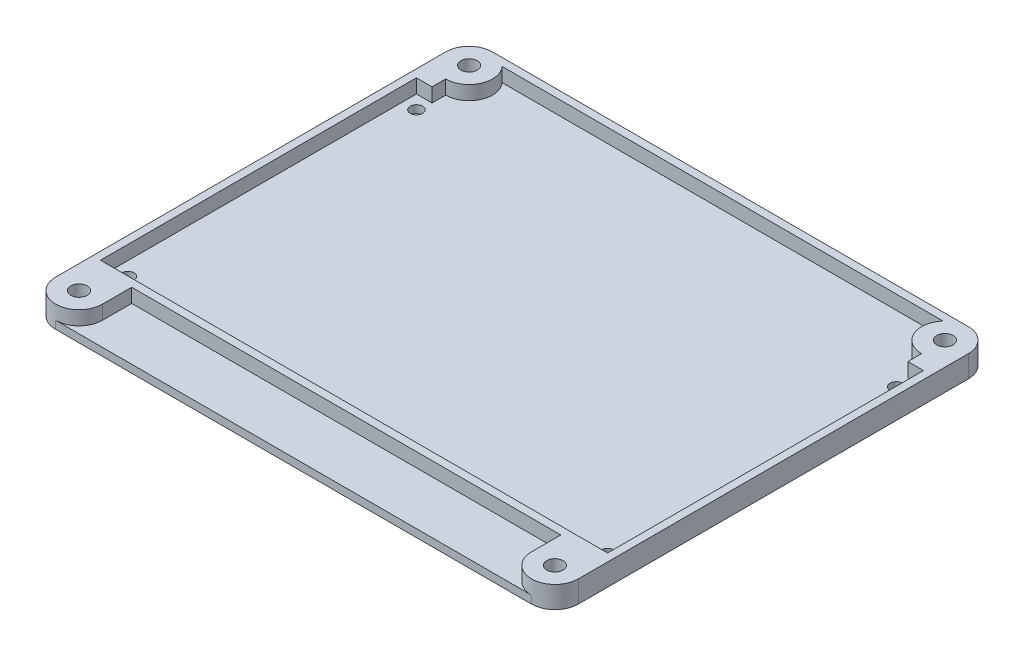
SolidWorks part; units mm, degrees
ref_plane "前视基准面" through (0, 0, 0) normal (0, 0, 1) x (1, 0, 0)
ref_plane "上视基准面" through (0, 0, 0) normal (0, 1, 0) x (1, 0, 0)
ref_plane "右视基准面" through (0, 0, 0) normal (1, 0, 0) x (0, 0, -1)
other "Configuration Table"
sketch "草图1" plane through (0, 0, 0) normal (0, 1, 0) x (1, 0, 0)
  line L0 (32.2763, 0) -> (161.2763, 0)
  line L1 (161.2763, 0) -> (161.2763, 80)
  line L2 (161.2763, 80) -> (32.2763, 80)
  line L3 (32.2763, 80) -> (32.2763, 0)
  circle A0 centre (35.2763, 77) radius 1.6
  circle A1 centre (158.2763, 77) radius 1.6
  circle A2 centre (158.2763, 3) radius 1.6
  circle A3 centre (35.2763, 3) radius 1.6
extrude "凸台-拉伸1" add sketch "草图1" along normal blind 2
sketch "草图2" plane through (0, 2, 0) normal (0, 1, 0) x (1, 0, 0)
  line L1 (35.7763, 96) -> (157.7763, 96)
  line L2 (157.7763, -16) -> (35.7763, -16)
  line L9 (29.7763, 90) -> (29.7763, -10)
  line L11 (163.7763, 90) -> (163.7763, -10)
  line L13 (161.2763, 0) -> (161.2763, 80) construction
  line L14 (161.2763, 80) -> (32.2763, 80) construction
  line L15 (32.2763, 80) -> (32.2763, 0) construction
  line L16 (32.2763, 0) -> (161.2763, 0) construction
  line L17 (161.2763, 0) -> (161.2763, 80)
  line L18 (161.2763, 80) -> (32.2763, 80)
  line L19 (32.2763, 80) -> (32.2763, 0)
  line L20 (32.2763, 0) -> (161.2763, 0)
  circle A0 centre (35.7763, -10) radius 2.1
  circle A1 centre (157.7763, -10) radius 2.1
  circle A2 centre (157.7763, 90) radius 2.1
  circle A3 centre (35.7763, 90) radius 2.1
  arc A4 (35.7763, 96) -> (29.7763, 90) centre (35.7763, 90) ccw
  arc A5 (163.7763, 90) -> (157.7763, 96) centre (157.7763, 90) ccw
  arc A6 (157.7763, -16) -> (163.7763, -10) centre (157.7763, -10) ccw
  arc A7 (29.7763, -10) -> (35.7763, -16) centre (35.7763, -10) ccw
  dimension "D1" = 6
extrude "凸台-拉伸2" add sketch "草图2" against normal blind 2
sketch "草图3" plane through (0, 2, 0) normal (0, 1, 0) x (1, 0, 0)
  line L1 (41.7763, -10) -> (41.7763, -2.5)
  line L24 (31.7763, -0.5) -> (161.7763, -0.5)
  line L25 (161.7763, -0.5) -> (161.7763, 80.5)
  line L27 (31.7763, 80.5) -> (31.7763, -0.5)
  line L28 (29.7763, 90) -> (29.7763, -10)
  line L29 (35.7763, -16) -> (157.7763, -16)
  line L30 (163.7763, -10) -> (163.7763, 90)
  line L31 (157.7763, 96) -> (35.7763, 96)
  line L32 (29.7763, 90) -> (29.7763, -10)
  line L34 (163.7763, -10) -> (163.7763, 90)
  line L44 (41.7763, -2.5) -> (151.7763, -2.5)
  line L46 (31.7763, -2.5) -> (161.7763, -2.5) construction
  line L47 (151.7763, -10) -> (151.7763, -2.5)
  line L49 (31.7763, 80.5) -> (35.7763, 80.5)
  line L51 (35.7763, 96) -> (157.7763, 96)
  line L52 (35.7763, 80.5) -> (35.7763, 84)
  line L53 (96.7763, 94) -> (40.2484, 94)
  line L54 (96.7763, 94) -> (153.3041, 94)
  line L55 (157.7763, 80.5) -> (157.7763, 84)
  line L56 (157.7763, 80.5) -> (161.7763, 80.5)
  arc A7 (35.7763, -16) -> (41.7763, -10) centre (35.7763, -10) ccw
  arc A9 (157.7763, -16) -> (151.7763, -10) centre (157.7763, -10) cw
  arc A12 (35.7763, 96) -> (29.7763, 90) centre (35.7763, 90) ccw
  arc A13 (29.7763, -10) -> (35.7763, -16) centre (35.7763, -10) ccw
  arc A14 (157.7763, -16) -> (163.7763, -10) centre (157.7763, -10) ccw
  arc A15 (163.7763, 90) -> (157.7763, 96) centre (157.7763, 90) ccw
  arc A17 (29.7763, -10) -> (35.7763, -16) centre (35.7763, -10) ccw
  arc A18 (157.7763, -16) -> (163.7763, -10) centre (157.7763, -10) ccw
  circle A23 centre (35.7763, -10) radius 2.1 construction
  circle A25 centre (35.7763, -10) radius 2.1
  circle A26 centre (35.7763, 90) radius 2.1 construction
  circle A27 centre (35.7763, 90) radius 2.1
  circle A28 centre (157.7763, 90) radius 2.1 construction
  circle A29 centre (157.7763, 90) radius 2.1
  circle A30 centre (157.7763, -10) radius 2.1 construction
  circle A31 centre (157.7763, -10) radius 2.1
  arc A32 (35.7763, 96) -> (29.7763, 90) centre (35.7763, 90) ccw
  arc A33 (153.3041, 94) -> (157.7763, 84) centre (157.7763, 90) ccw
  arc A34 (163.7763, 90) -> (157.7763, 96) centre (157.7763, 90) ccw
  arc A35 (35.7763, 84) -> (40.2484, 94) centre (35.7763, 90) ccw
  point P29 (31.7763, 40)
  point P30 (161.7763, 40)
  dimension "D1" = 0
  dimension "D2" = 2
extrude "凸台-拉伸3" add sketch "草图3" along normal blind 3.6
sketch "草图4" plane through (0, 0, 0) normal (0, -1, 0) x (1, 0, 0)
  line L45 (149.2763, -80.2) -> (142.4763, -80.2)
  line L70 (56.5763, -92.5) -> (50.7763, -92.5)
  line L71 (56.5763, -92.5) -> (56.5763, -85.7)
  line L72 (136.9763, 12.5) -> (142.7763, 12.5)
  line L73 (149.2763, 6) -> (149.2763, 0.2)
  line L74 (44.2763, 0.2) -> (51.0763, 0.2)
  line L75 (51.0763, -80.2) -> (56.5763, -85.7)
  line L76 (50.7763, 12.5) -> (56.5763, 12.5)
  line L78 (44.2763, -86) -> (44.2763, -80.2)
  line L79 (136.9763, -92.5) -> (136.9763, -85.7)
  line L80 (56.5763, 12.5) -> (56.5763, 5.7)
  line L81 (136.9763, 12.5) -> (136.9763, 5.7)
  line L82 (142.7763, -92.5) -> (136.9763, -92.5)
  line L83 (149.2763, 0.2) -> (142.4763, 0.2)
  line L84 (142.4763, 0.2) -> (136.9763, 5.7)
  line L85 (56.5763, 5.7) -> (51.0763, 0.2)
  line L86 (44.2763, 0.2) -> (44.2763, 6)
  line L87 (149.2763, -80.2) -> (149.2763, -86)
  line L88 (136.9763, -85.7) -> (142.4763, -80.2)
  line L89 (44.2763, -80.2) -> (51.0763, -80.2)
  circle A2 centre (142.7763, 6) radius 1.6
  arc A10 (50.7763, 12.5) -> (44.2763, 6) centre (50.7763, 6) ccw
  circle A15 centre (50.7763, -86) radius 1.6
  arc A20 (149.2763, 6) -> (142.7763, 12.5) centre (142.7763, 6) ccw
  arc A21 (44.2763, -86) -> (50.7763, -92.5) centre (50.7763, -86) ccw
  circle A22 centre (142.7763, -86) radius 1.6
  circle A39 centre (50.7763, 6) radius 1.6
  arc A44 (142.7763, -92.5) -> (149.2763, -86) centre (142.7763, -86) ccw
  point P34 (68.4522, -47.9433)
  point P78 (90.0662, 0)
  point P79 (90.0662, -49.8906)
extrude "凸台-拉伸4" add sketch "草图4" along normal blind 3
